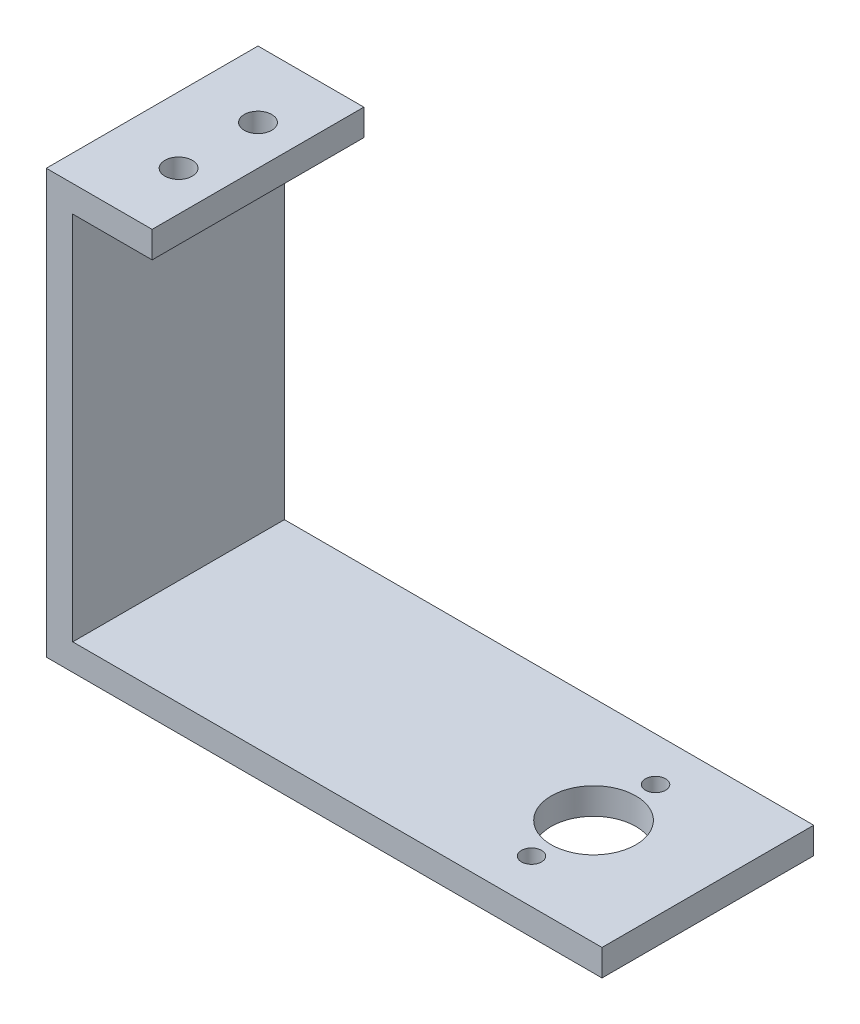
SolidWorks part; units mm, degrees
ref_plane "Front Plane" through (0, 0, 0) normal (0, 0, 1) x (1, 0, 0)
ref_plane "Top Plane" through (0, 0, 0) normal (0, 1, 0) x (1, 0, 0)
ref_plane "Right Plane" through (0, 0, 0) normal (1, 0, 0) x (0, 0, -1)
sketch "Sketch1" plane through (0, 0, 0) normal (0, 0, 1) x (1, 0, 0)
  line L0 (-17.0593, 26.9872) -> (-29.7593, 26.9872)
  line L1 (-29.7593, 26.9872) -> (-29.7593, -23.8128)
  line L2 (-29.7593, -23.8128) -> (36.9157, -23.8128)
  line L3 (-17.0593, 23.8122) -> (-26.5843, 23.8122)
  line L4 (-26.5843, 23.8122) -> (-26.5843, -20.6378)
  line L5 (-26.5843, -20.6378) -> (36.9157, -20.6378)
  line L6 (-17.0593, 26.9872) -> (-17.0593, 23.8122)
  line L7 (36.9157, -23.8128) -> (36.9157, -20.6378)
  dimension "D2" = 12.7
  dimension "D3" = 44.45
  dimension "D4" = 63.5
  dimension "D1" = 3.175
extrude "Boss-Extrude1" add sketch "Sketch1" along normal blind 25.4
hole_wizard "M4x0.7 Tapped Hole1" positions "Sketch6" profile "Sketch5" tap size "M4x0.7" standard "ANSI Metric"
sketch "Sketch6" plane through (0, 26.9872, 0) normal (0, 1, 0) x (1, 0, 0)
  line L1 (-17.0593, -25.4) -> (-17.0593, 0) construction
  line L2 (-17.0593, 0) -> (-29.7593, 0) construction
  point P0 (-21.8218, -7.9375)
  point P2 (-21.8218, -17.4625)
  dimension "D1" = 4.7625
  dimension "D2" = 9.525
  dimension "D3" = 7.9375
sketch "Sketch5" plane through (-21.8218, 26.9872, 7.9375) normal (1, 0, 0) x (0, 0, 1)
  line L0 (0, 0) -> (0, 10.8974)
  line L1 (0, 10.8974) -> (1.65, 9.906)
  line L2 (1.65, 9.906) -> (1.65, 0)
  line L5 (1.65, 0) -> (0, 0)
  line L10 (0, 10.8974) -> (-1.65, 9.906) construction
  line L11 (0, -6.35) -> (0, 107.95) construction
  dimension "Tap Drill Dia." = 3.3
  dimension "Tap Drill Depth" = 9.906
  dimension "Drill Angle" = 118
sketch "Sketch7" plane through (0, -23.8128, 0) normal (0, -1, 0) x (1, 0, 0)
  line L0 (-29.7593, 25.4) -> (36.9157, 25.4) construction
  line L2 (-26.5843, 25.4) -> (-26.5843, 0) construction
  circle A0 centre (23.1997, 12.7) radius 5.08
  circle A1 centre (23.1997, 12.7) radius 7.4422 construction
  circle A2 centre (23.1997, 5.2578) radius 1.2065
  circle A3 centre (23.1997, 20.1422) radius 1.2065
  dimension "D3" = 10.16
  dimension "D4" = 14.8844
  dimension "D5" = 2.413
  dimension "D1" = 12.7
  dimension "D2" = 49.784
extrude "Cut-Extrude1" cut sketch "Sketch7" against normal up to next
